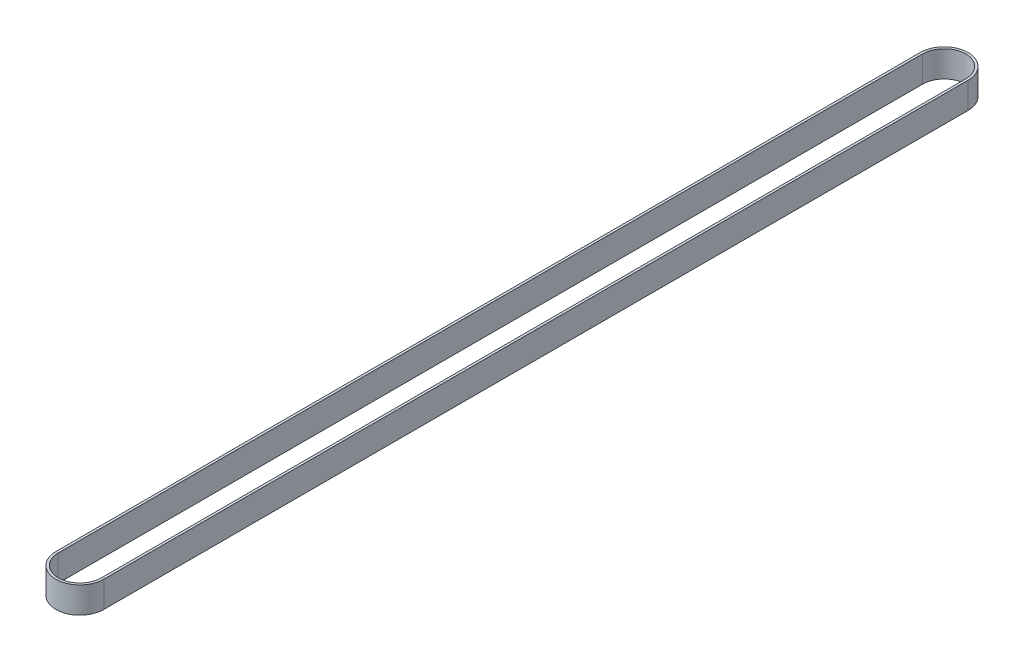
SolidWorks part; units mm, degrees
ref_plane "Front Plane" through (0, 0, 0) normal (0, 0, 1) x (1, 0, 0)
ref_plane "Top Plane" through (0, 0, 0) normal (0, 1, 0) x (1, 0, 0)
ref_plane "Right Plane" through (0, 0, 0) normal (1, 0, 0) x (0, 0, -1)
sketch "Sketch1" plane through (0, 0, 0) normal (0, 1, 0) x (1, 0, 0)
  line L0 (-9.05, 0) -> (-9.05, -362.5)
  line L1 (9.05, -362.5) -> (9.05, 0)
  line L2 (-10.05, 0) -> (-10.05, -362.5)
  line L3 (10.05, -362.5) -> (10.05, 0)
  arc A0 (-9.05, -362.5) -> (9.05, -362.5) centre (0, -362.5) ccw
  arc A1 (9.05, 0) -> (-9.05, 0) centre (0, 0) ccw
  arc A2 (-10.05, -362.5) -> (10.05, -362.5) centre (0, -362.5) ccw
  arc A3 (10.05, 0) -> (-10.05, 0) centre (0, 0) ccw
  dimension "D1" = 1
extrude "Boss-Extrude1" add sketch "Sketch1" along normal blind 11
